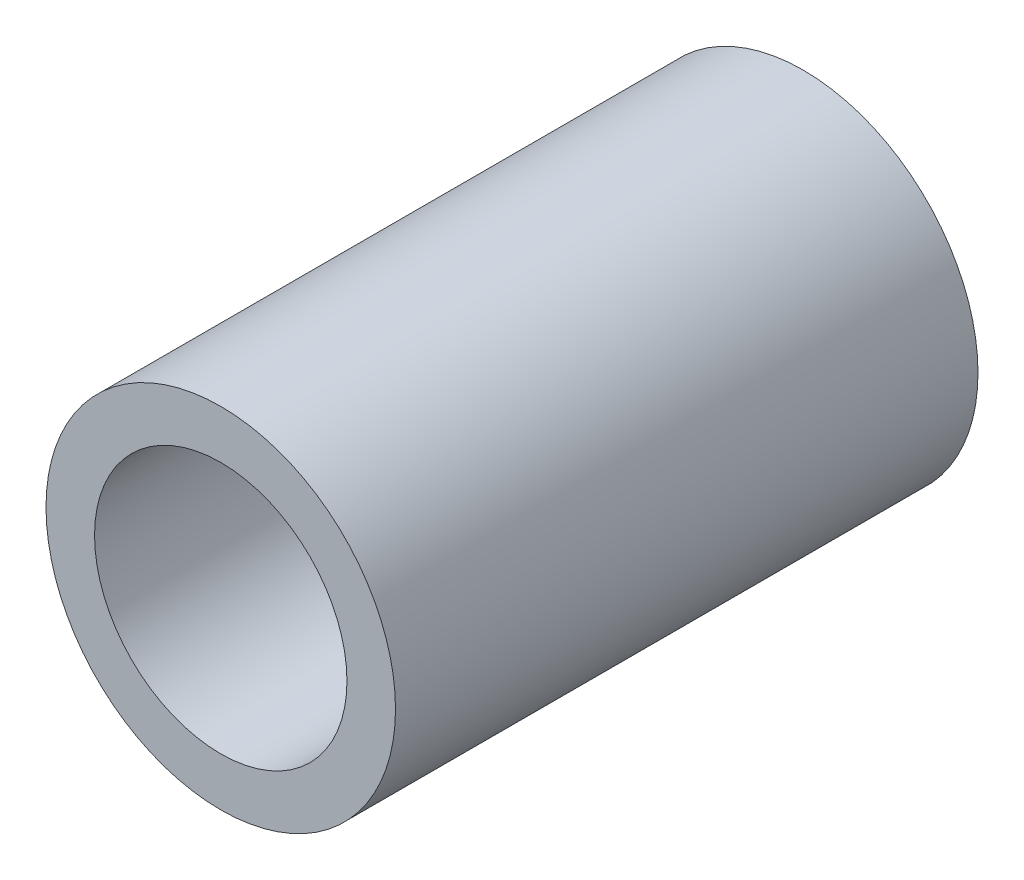
SolidWorks part; units mm, degrees
ref_plane "Alzado" through (0, 0, 0) normal (0, 0, 1) x (1, 0, 0)
ref_plane "Planta" through (0, 0, 0) normal (0, 1, 0) x (1, 0, 0)
ref_plane "Vista lateral" through (0, 0, 0) normal (1, 0, 0) x (0, 0, -1)
sketch "Croquis1" plane through (0, 0, 0) normal (0, 0, 1) x (1, 0, 0)
  circle A0 centre (0, 0) radius 3.25
  circle A1 centre (0, 0) radius 4.5
  dimension "D1" = 6.5
  dimension "D2" = 9
extrude "Saliente-Extruir1" add sketch "Croquis1" along normal blind 15
